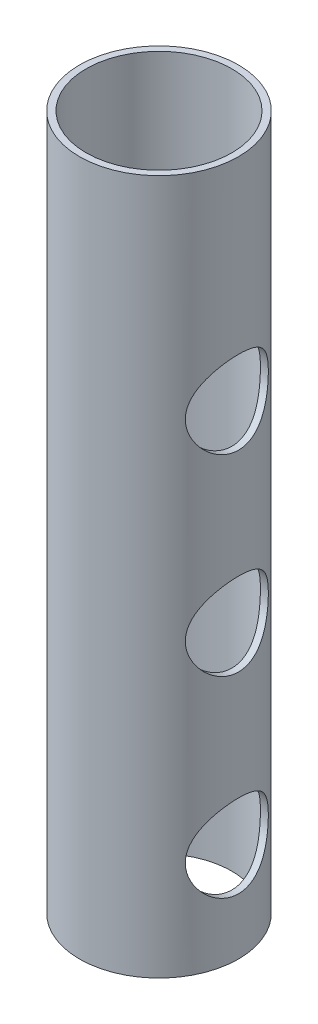
SolidWorks part; units mm, degrees
material "PTFE (general)"
ref_plane "Front Plane" through (0, 0, 0) normal (0, 0, 1) x (1, 0, 0)
ref_plane "Top Plane" through (0, 0, 0) normal (0, 1, 0) x (1, 0, 0)
ref_plane "Right Plane" through (0, 0, 0) normal (1, 0, 0) x (0, 0, -1)
sketch "Sketch1" plane through (0, 0, 0) normal (0, 1, 0) x (1, 0, 0)
  circle A0 centre (0, 0) radius 24
  circle A1 centre (0, 0) radius 22
  dimension "D1" = 2
  dimension "D2" = 44
extrude "Boss-Extrude1" add sketch "Sketch1" along normal blind 209.8
sketch "Sketch2" plane through (0, 0, 0) normal (1, 0, 0) x (0, 0, -1)
  line L0 (22, 209.8) -> (-22, 209.8) construction
  circle A0 centre (0, 145.6) radius 12.53
  circle A1 centre (0, 87.6) radius 12.53
  circle A2 centre (0, 29.6) radius 12.53
  dimension "D2" = 25.06
  dimension "D3" = 25.06
  dimension "D4" = 25.06
  dimension "D1" = 64.2
  dimension "D5" = 58
  dimension "D6" = 58
extrude "Cut-Extrude1" cut sketch "Sketch2" along normal through all
